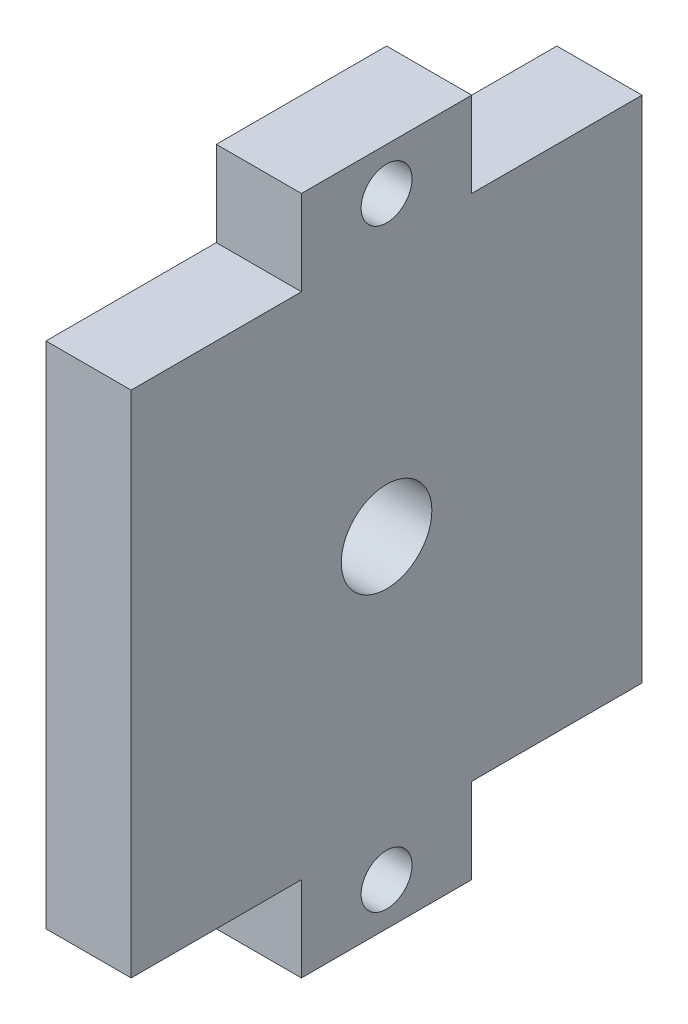
SolidWorks part; units mm, degrees
material "Beech"
ref_plane "Front Plane" through (0, 0, 0) normal (0, 0, 1) x (1, 0, 0)
ref_plane "Top Plane" through (0, 0, 0) normal (0, 1, 0) x (1, 0, 0)
ref_plane "Right Plane" through (0, 0, 0) normal (1, 0, 0) x (0, 0, -1)
sketch "Sketch1" plane through (0, 0, 0) normal (1, 0, 0) x (0, 0, -1)
  line L1 (-19.05, -25.3365) -> (19.05, -25.3365)
  line L2 (-19.05, -25.3365) -> (-19.05, 25.3365)
  line L3 (-19.05, 25.3365) -> (19.05, 25.3365)
  line L4 (19.05, -25.3365) -> (19.05, 25.3365)
  line L5 (-19.05, -25.3365) -> (19.05, 25.3365) construction
  line L6 (-19.05, 25.3365) -> (19.05, -25.3365) construction
  point P0 (0, 0)
  dimension "D1" = 38.1
  dimension "D2" = 50.673
extrude "Boss-Extrude1" add sketch "Sketch1" along normal mid plane 6.35
sketch "Sketch2" plane through (3.175, 0, 0) normal (1, 0, 0) x (0, 0, -1)
  line L0 (0, 25.3365) -> (0, -25.3365) construction
  line L1 (-19.05, 25.3365) -> (-6.35, 25.3365)
  line L2 (-19.05, 25.3365) -> (-19.05, 18.9865)
  line L3 (-19.05, 18.9865) -> (-6.35, 18.9865)
  line L4 (-6.35, 25.3365) -> (-6.35, 18.9865)
  line L5 (19.05, 25.3365) -> (-19.05, 25.3365) construction
  line L6 (-19.05, -25.3365) -> (19.05, -25.3365) construction
  dimension "D1" = 6.35
  dimension "D2" = 6.35
extrude "Cut-Extrude1" cut sketch "Sketch2" against normal up to next
mirror "Mirror1" about plane through (0, 0, 0) normal (0, 0, 1) of "Cut-Extrude1"
hole_wizard "#6 Clearance Hole1" positions "Sketch4" profile "Sketch3" hole size "#6" standard "ANSI Inch"
sketch "Sketch4" plane through (3.175, 0, 0) normal (1, 0, 0) x (0, 0, -1)
  line L0 (0, 25.3365) -> (0, -25.3365) construction
  line L1 (6.35, 25.3365) -> (-6.35, 25.3365) construction
  line L2 (-19.05, -25.3365) -> (19.05, -25.3365) construction
  line L4 (-6.35, 22.1615) -> (6.35, 22.1615) construction
  line L5 (-6.35, 18.9865) -> (-6.35, 25.3365) construction
  line L6 (6.35, 18.9865) -> (6.35, 25.3365) construction
  point P0 (0, 22.1615)
sketch "Sketch3" plane through (3.175, 22.1615, 0) normal (0, 1, 0) x (0, 0, -1)
  line L0 (0, 0) -> (0, 10.0308)
  line L1 (0, 10.0308) -> (1.8986, 8.89)
  line L2 (1.8986, 8.89) -> (1.8986, 0)
  line L5 (1.8986, 0) -> (0, 0)
  line L10 (0, 10.0308) -> (-1.8987, 8.89) construction
  line L11 (0, -6.35) -> (0, 107.95) construction
  dimension "Hole Dia." = 3.7973
  dimension "Hole Depth" = 8.89
  dimension "Drill Angle" = 118
mirror "Mirror2" about plane through (0, 0, 0) normal (0, 1, 0) of "#6 Clearance Hole1", "Mirror1", "Cut-Extrude1"
hole_wizard "1/4 Clearance Hole1" positions "Sketch6" profile "Sketch5" hole size "1/4" standard "ANSI Inch" end condition up to next
sketch "Sketch6" plane through (3.175, 0, 0) normal (1, 0, 0) x (0, 0, -1)
  point P0 (0, 0)
sketch "Sketch5" plane through (3.175, 0, 0) normal (0, 1, 0) x (0, 0, -1)
  line L0 (0, 0) -> (0, 6.35)
  line L1 (0, 6.35) -> (3.3782, 6.35)
  line L2 (3.3782, 6.35) -> (3.3782, 0)
  line L5 (3.3782, 0) -> (0, 0)
  line L11 (0, -6.35) -> (0, 107.95) construction
  dimension "Thru Hole Dia." = 6.7564
  dimension "Thru Hole Depth" = 6.35
